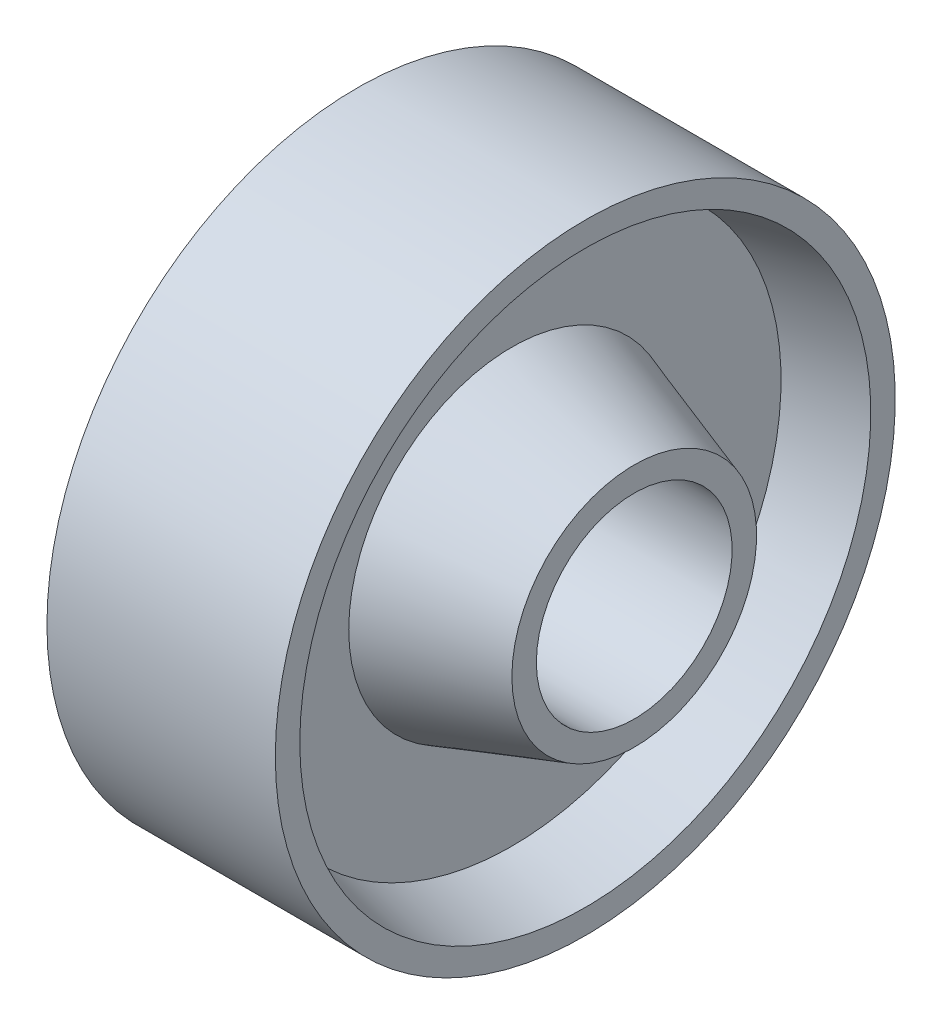
SolidWorks part; units mm, degrees
material "Chromium Copper, UNS C18200"
ref_plane "Front Plane" through (0, 0, 0) normal (0, 0, 1) x (1, 0, 0)
ref_plane "Top Plane" through (0, 0, 0) normal (0, 1, 0) x (1, 0, 0)
ref_plane "Right Plane" through (0, 0, 0) normal (1, 0, 0) x (0, 0, -1)
sketch "Sketch4" plane through (0, 0, 0) normal (0, 0, 1) x (1, 0, 0)
  line L0 (0, 0) -> (20, 0)
  line L1 (0, 0) -> (-20, 0)
  line L2 (20, 0) -> (20, 3)
  line L16 (20, 3) -> (5, 8)
  line L17 (5, 8) -> (5, 21)
  line L18 (5, 21) -> (14, 23)
  line L19 (14, 23) -> (14, 26)
  line L21 (-14, 26) -> (-14, 23)
  line L22 (-14, 23) -> (-5, 21)
  line L23 (-5, 21) -> (-5, 8)
  line L25 (-20, 0) -> (-20, 3)
  line L26 (-20, 3) -> (-5, 8)
  line L27 (0, 0) -> (0, 40.814) construction
  line L28 (14, 26) -> (0, 26)
  line L29 (0, 26) -> (-14, 26)
  line L30 (-20, 0) -> (-20, -12) construction
  line L31 (-20, -12) -> (25.5275, -12) construction
  dimension "D9" = 3
  dimension "D15" = 14
  dimension "D1" = 20
  dimension "D2" = 20
  dimension "D3" = 3
  dimension "D4" = 13
  dimension "D5" = 5
  dimension "D6" = 14
  dimension "D7" = 5
  dimension "D8" = 13
  dimension "D10" = 3
  dimension "D11" = 3
  dimension "D12" = 5
  dimension "D13" = 5
  dimension "D14" = 10
  dimension "D16" = 2
  dimension "D17" = 15.8114
  dimension "D18" = 12
  dimension "D19" = 2
  dimension "D20" = 9.2195
revolve "Revolve10" add sketch "Sketch4" angle 360 about L31
